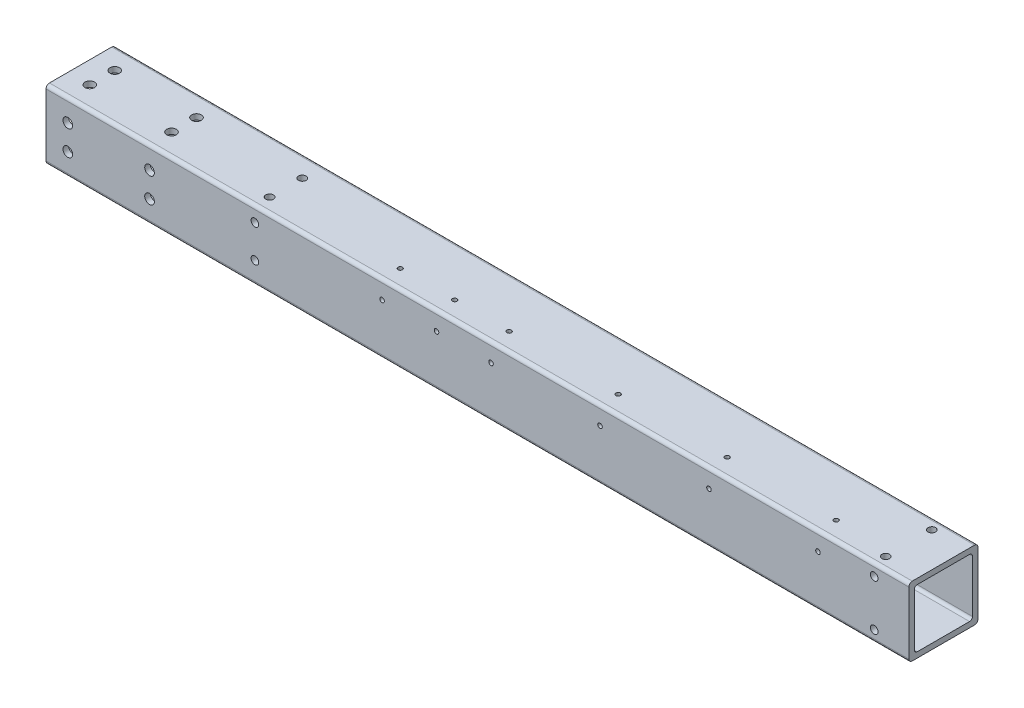
SolidWorks part; units mm, degrees
material "ASTM A36 Steel"
ref_plane "Front" through (0, 0, 0) normal (0, 0, 1) x (1, 0, 0)
ref_plane "Top" through (0, 0, 0) normal (0, 1, 0) x (1, 0, 0)
ref_plane "Right" through (0, 0, 0) normal (1, 0, 0) x (0, 0, -1)
sketch "Sketch1" plane through (0, 0, 0) normal (1, 0, 0) x (0, 0, -1)
  line L0 (-16.002, 0) -> (-19.05, 0) construction
  line L1 (17.145, -19.05) -> (-17.145, -19.05) construction
  line L2 (19.05, -17.145) -> (19.05, 17.145) construction
  line L3 (17.145, 19.05) -> (-17.145, 19.05) construction
  line L4 (-19.05, -17.145) -> (-19.05, 17.145) construction
  line L5 (19.05, -19.05) -> (-19.05, 19.05) construction
  line L6 (19.05, 19.05) -> (-19.05, -19.05) construction
  line L7 (14.4018, 16.002) -> (-14.4018, 16.002) construction
  line L8 (16.002, 14.4018) -> (16.002, -14.4018) construction
  line L9 (14.4018, -16.002) -> (-14.4018, -16.002) construction
  line L10 (-16.002, 14.4018) -> (-16.002, -14.4018) construction
  line L11 (16.002, 16.002) -> (-16.002, -16.002) construction
  line L12 (16.002, -16.002) -> (-16.002, 16.002) construction
  line L13 (0, -16.002) -> (0, -19.05) construction
  line L14 (16.002, -14.4018) -> (16.002, -19.05) construction
  line L15 (16.002, 0) -> (19.05, 0) construction
  line L16 (16.002, -19.05) -> (19.05, -19.05) construction
  arc A0 (-14.4018, -16.002) -> (-16.002, -14.4018) centre (-14.4018, -14.4018) cw construction
  arc A1 (16.002, -14.4018) -> (14.4018, -16.002) centre (14.4018, -14.4018) cw construction
  arc A2 (14.4018, 16.002) -> (16.002, 14.4018) centre (14.4018, 14.4018) cw construction
  arc A3 (-14.4018, 16.002) -> (-16.002, 14.4018) centre (-14.4018, 14.4018) ccw construction
  arc A4 (17.145, -19.05) -> (19.05, -17.145) centre (17.145, -17.145) ccw construction
  arc A5 (19.05, 17.145) -> (17.145, 19.05) centre (17.145, 17.145) ccw construction
  arc A6 (-17.145, 19.05) -> (-19.05, 17.145) centre (-17.145, 17.145) ccw construction
  arc A7 (-17.145, -19.05) -> (-19.05, -17.145) centre (-17.145, -17.145) cw construction
  point P0 (0, 0)
  point P6 (0, 0)
  dimension "D2" = 1.6002
  dimension "D3" = 1.905
  dimension "Outside Width" = 38.1
  dimension "Ouside Height" = 38.1
  dimension "Inside Height" = 32.004
  dimension "Wall Thickness" = 3.048
sketch "Sketch2" plane through (0, 0, 0) normal (0, 0, 1) x (1, 0, 0)
  line L0 (-237.5, 0) -> (237.5, 0) construction
  point P3 (-202.448, 0)
  point P4 (202.448, 0)
  dimension "Length" = 475
  dimension "D1" = 35.052
  dimension "D2" = 35.052
sketch "Sketch4" plane through (0, 0, 0) normal (1, 0, 0) x (0, 0, -1)
  line L8 (19.05, -17.145) -> (19.05, 17.145)
  line L9 (17.145, 19.05) -> (-17.145, 19.05)
  line L10 (-19.05, -17.145) -> (-19.05, 17.145)
  line L11 (17.145, -19.05) -> (-17.145, -19.05)
  line L12 (16.002, 14.4018) -> (16.002, -14.4018)
  line L13 (14.4018, -16.002) -> (-14.4018, -16.002)
  line L14 (-16.002, 14.4018) -> (-16.002, -14.4018)
  line L15 (14.4018, 16.002) -> (-14.4018, 16.002)
  arc A8 (19.05, 17.145) -> (17.145, 19.05) centre (17.145, 17.145) ccw
  arc A9 (-17.145, 19.05) -> (-19.05, 17.145) centre (-17.145, 17.145) ccw
  arc A10 (-19.05, -17.145) -> (-17.145, -19.05) centre (-17.145, -17.145) ccw
  arc A11 (17.145, -19.05) -> (19.05, -17.145) centre (17.145, -17.145) ccw
  arc A12 (14.4018, -16.002) -> (16.002, -14.4018) centre (14.4018, -14.4018) ccw
  arc A13 (-16.002, -14.4018) -> (-14.4018, -16.002) centre (-14.4018, -14.4018) ccw
  arc A14 (-14.4018, 16.002) -> (-16.002, 14.4018) centre (-14.4018, 14.4018) ccw
  arc A15 (16.002, 14.4018) -> (14.4018, 16.002) centre (14.4018, 14.4018) ccw
extrude "Boss-Extrude1" add sketch "Sketch4" along normal up to vertex (237.5 mm away) and the other way up to vertex (237.5 mm away)
hole_wizard "Tap Drill for M5x0.8 Tap1" positions "Sketch5" profile "Sketch6" hole size "M5x0.8" standard "ANSI Metric"
sketch "Sketch5" plane through (0, 19.05, 0) normal (0, 1, 0) x (1, 0, 0)
  line L0 (-122.5, -10.95) -> (-122.5, 7.05) construction
  line L2 (-237.5, 17.145) -> (-237.5, -17.145) construction
  line L3 (237.5, 19.05) -> (-237.5, 19.05) construction
  point P0 (-122.5, 7.05)
  point P2 (-122.5, -10.95)
  point P20 (-122.5, -1.95)
  dimension "D1" = 18
  dimension "D2" = 115
  dimension "D3" = 21
sketch "Sketch6" plane through (-122.5, 19.05, -7.05) normal (1, 0, 0) x (0, 0, 1)
  line L0 (0, 0) -> (0, 3.048)
  line L1 (0, 3.048) -> (2.1, 3.048)
  line L2 (2.1, 3.048) -> (2.1, 0)
  line L5 (2.1, 0) -> (0, 0)
  line L11 (0, -6.35) -> (0, 107.95) construction
  dimension "Thru Hole Dia." = 4.2
  dimension "Thru Hole Depth" = 3.048
ref_plane "Plane1" through (0, 0, 0) normal (0, -0.7071, 0.7071) x (1, 0, 0)
hole_wizard "Tap Drill for M3x0.5 Tap1" positions "Sketch8" profile "Sketch9" hole size "M3x0.5" standard "ANSI Metric"
sketch "Sketch8" plane through (0, 0, 19.05) normal (0, 0, 1) x (1, 0, 0)
  line L0 (237.5, 17.145) -> (237.5, -17.145) construction
  line L1 (237.5, 19.05) -> (-237.5, 19.05) construction
  line L3 (-52.5, 9.05) -> (7.5, 9.05) construction
  point P0 (187.5, 9.05)
  point P5 (127.5, 9.05)
  point P6 (67.5, 9.05)
  point P7 (7.5, 9.05)
  point P8 (-52.5, 9.05)
  point P27 (-22.5, 9.05)
  dimension "D2" = 60
  dimension "D3" = 50
  dimension "D4" = 10
  dimension "D1" = 5
sketch "Sketch9" plane through (187.5, 9.05, 19.05) normal (1, 0, 0) x (0, -1, 0)
  line L0 (0, 0) -> (0, 3.048)
  line L1 (0, 3.048) -> (1.25, 3.048)
  line L2 (1.25, 3.048) -> (1.25, 0)
  line L5 (1.25, 0) -> (0, 0)
  line L11 (0, -6.35) -> (0, 107.95) construction
  dimension "Thru Hole Dia." = 2.5
  dimension "Thru Hole Depth" = 3.048
hole_wizard "Tap Drill for M5x0.8 Tap2" positions "Sketch21" profile "Sketch22" hole size "M5x0.8" standard "ANSI Metric"
sketch "Sketch21" plane through (0, 0, 19.05) normal (0, 0, 1) x (1, 0, 0)
  line L0 (218.45, 12.7) -> (218.45, -12.7) construction
  line L2 (237.5, 17.145) -> (237.5, -17.145) construction
  point P0 (218.45, 12.7)
  point P2 (218.45, -12.7)
  point P11 (237.5, 0)
  point P12 (218.45, 0)
  dimension "D1" = 19.05
  dimension "D2" = 25.4
sketch "Sketch22" plane through (218.45, 12.7, 19.05) normal (1, 0, 0) x (0, -1, 0)
  line L0 (0, 0) -> (0, 6.2618)
  line L1 (0, 6.2618) -> (2.1, 5)
  line L2 (2.1, 5) -> (2.1, 0)
  line L5 (2.1, 0) -> (0, 0)
  line L10 (0, 6.2618) -> (-2.1, 5) construction
  line L11 (0, -6.35) -> (0, 107.95) construction
  dimension "Hole Dia." = 4.2
  dimension "Hole Depth" = 5
  dimension "Drill Angle" = 118
mirror "Mirror1" about plane through (0, 0, 0) normal (0, -0.7071, 0.7071) of "Tap Drill for M5x0.8 Tap2", "Tap Drill for M5x0.8 Tap1", "Tap Drill for M3x0.5 Tap1"
ref_plane "Plane2" through (0, 0, 0) normal (0, 0.7071, 0.7071) x (1, 0, 0)
sketch "Sketch12" plane through (0, 19.05, 0) normal (0, 1, 0) x (1, 0, 0)
  line L0 (-225.5, -6.95) -> (-225.5, 6.8) construction
  line L2 (-237.5, -1.95) -> (-170.3884, -1.95) construction
  line L3 (-122.5, -10.95) -> (-122.5, 7.05) construction
  line L4 (-237.5, 17.145) -> (-237.5, -17.145) construction
  point P10 (-122.5, -1.95)
  dimension "D1" = 12
  dimension "D2" = 5
  dimension "D3" = 8.75
hole_wizard "M5 Clearance Hole1" positions "Sketch13" profile "Sketch15" hole size "M5" standard "ANSI Metric"
sketch "Sketch13" plane through (0, 19.05, 0) normal (0, 1, 0) x (1, 0, 0)
  line L1 (-237.5, 17.145) -> (-237.5, -17.145) construction
  point P0 (-225.5, 6.8)
  point P3 (-225.5, -6.95)
  point P6 (-180.5, -6.95)
  point P8 (-180.5, 6.8)
  dimension "D1" = 57
sketch "Sketch15" plane through (-225.5, 19.05, -6.8) normal (1, 0, 0) x (0, 0, 1)
  line L0 (0, 0) -> (0, 3.048)
  line L1 (0, 3.048) -> (2.65, 3.048)
  line L2 (2.65, 3.048) -> (2.65, 0)
  line L5 (2.65, 0) -> (0, 0)
  line L11 (0, -6.35) -> (0, 107.95) construction
  dimension "Thru Hole Dia." = 5.3
  dimension "Thru Hole Depth" = 3.048
mirror "Mirror2" about plane through (0, 0, 0) normal (0, -0.7071, 0.7071) of "M5 Clearance Hole1"
hole_wizard "Ø8.0 (8) Diameter Hole1" positions "Sketch17" profile "Sketch18" hole size "Ø8.0" standard "ANSI Metric"
sketch "Sketch17" plane through (0, 0, -16.002) normal (0, 0, 1) x (1, 0, 0)
  point P0 (-225.5, -6.8)
  point P3 (-225.5, 6.95)
  point P6 (-180.5, 6.95)
  point P9 (-180.5, -6.8)
sketch "Sketch18" plane through (-225.5, -6.8, -16.002) normal (1, 0, 0) x (0, -1, 0)
  line L0 (0, 0) -> (0, 3.048)
  line L1 (0, 3.048) -> (4, 3.048)
  line L2 (4, 3.048) -> (4, 0)
  line L5 (4, 0) -> (0, 0)
  line L11 (0, -6.35) -> (0, 107.95) construction
  dimension "Thru Hole Dia." = 8
  dimension "Thru Hole Depth" = 3.048
hole_wizard "Ø8.0 (8) Diameter Hole2" positions "Sketch19" profile "Sketch20" hole size "Ø8.0" standard "ANSI Metric"
sketch "Sketch19" plane through (0, -16.002, 0) normal (0, 1, 0) x (1, 0, 0)
  point P0 (-225.5, 6.8)
  point P3 (-225.5, -6.95)
  point P6 (-180.5, -6.95)
  point P9 (-180.5, 6.8)
sketch "Sketch20" plane through (-225.5, -16.002, -6.8) normal (1, 0, 0) x (0, 0, 1)
  line L0 (0, 0) -> (0, 3.048)
  line L1 (0, 3.048) -> (4, 3.048)
  line L2 (4, 3.048) -> (4, 0)
  line L5 (4, 0) -> (0, 0)
  line L11 (0, -6.35) -> (0, 107.95) construction
  dimension "Thru Hole Dia." = 8
  dimension "Thru Hole Depth" = 3.048
equation "\"D3@Sketch1\"=\"Outside Width@Sketch1\"*.05"
equation "\"D2@Sketch1\" = \"Inside Height@Sketch1\" * .05"
equation "\"D1@Sketch2\"=\"Outside Width@Sketch1\"-\"Wall Thickness@Sketch1\""
equation "\"D2@Sketch2\"=\"D1@Sketch2\""
